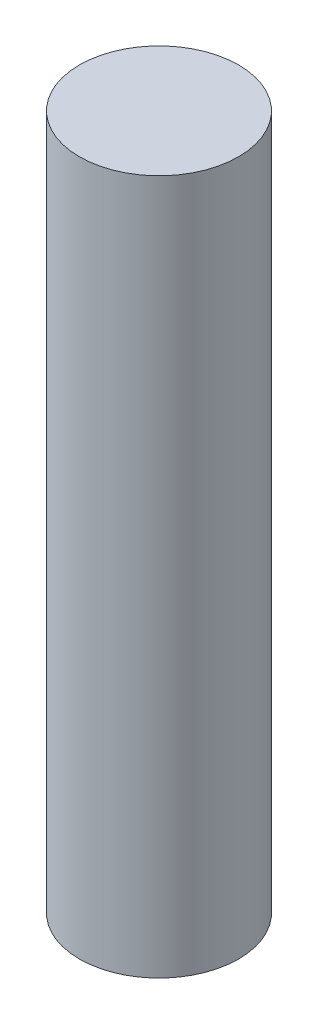
SolidWorks part; units mm, degrees
ref_plane "Front Plane" through (0, 0, 0) normal (0, 0, 1) x (1, 0, 0)
ref_plane "Top Plane" through (0, 0, 0) normal (0, 1, 0) x (1, 0, 0)
ref_plane "Right Plane" through (0, 0, 0) normal (1, 0, 0) x (0, 0, -1)
sketch "Sketch1" plane through (0, 0, 0) normal (0, 1, 0) x (1, 0, 0)
  circle A0 centre (0, 0) radius 75
  dimension "D1" = 150
extrude "Boss-Extrude1" add sketch "Sketch1" along normal blind 655
